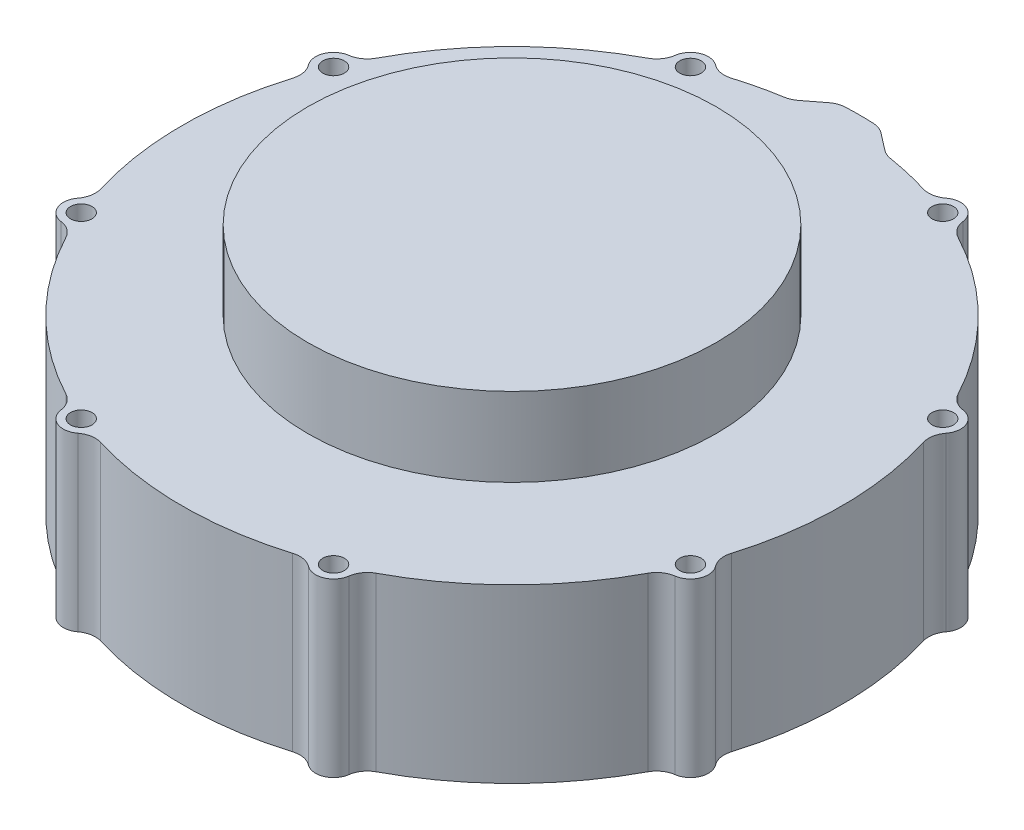
SolidWorks part; units mm, degrees
ref_plane "Спереди" through (0, 0, 0) normal (0, 0, 1) x (1, 0, 0)
ref_plane "Сверху" through (0, 0, 0) normal (0, 1, 0) x (1, 0, 0)
ref_plane "Справа" through (0, 0, 0) normal (1, 0, 0) x (0, 0, -1)
sketch "Эскиз1" plane through (0, 0, 0) normal (0, 1, 0) x (1, 0, 0)
  line L0 (0, 46) -> (0, -46) construction
  line L1 (-46, 0) -> (46, 0) construction
  line L2 (17.6034, 42.4985) -> (0, 0) construction
  line L3 (2.8896, 48.4138) -> (6.6554, 45.516)
  line L4 (-2.8896, 48.4138) -> (-6.6554, 45.516)
  arc A0 (-19.8863, 41.4793) -> (-41.4793, 19.8863) centre (0, 0) ccw
  circle A4 centre (17.6034, 42.4985) radius 1.5
  arc A5 (19.8863, 41.4793) -> (15.2686, 43.3921) centre (17.6034, 42.4985) ccw
  arc A6 (43.3921, 15.2686) -> (41.4793, 19.8863) centre (42.4985, 17.6034) ccw
  circle A7 centre (42.4985, 17.6034) radius 1.5
  arc A8 (41.4793, -19.8863) -> (43.3921, -15.2686) centre (42.4985, -17.6034) ccw
  circle A9 centre (42.4985, -17.6034) radius 1.5
  arc A10 (15.2686, -43.3921) -> (19.8863, -41.4793) centre (17.6034, -42.4985) ccw
  circle A11 centre (17.6034, -42.4985) radius 1.5
  arc A12 (-19.8863, -41.4793) -> (-15.2686, -43.3921) centre (-17.6034, -42.4985) ccw
  circle A13 centre (-17.6034, -42.4985) radius 1.5
  arc A14 (-43.3921, -15.2686) -> (-41.4793, -19.8863) centre (-42.4985, -17.6034) ccw
  circle A15 centre (-42.4985, -17.6034) radius 1.5
  arc A16 (-41.4793, 19.8863) -> (-43.3921, 15.2686) centre (-42.4985, 17.6034) ccw
  circle A17 centre (-42.4985, 17.6034) radius 1.5
  arc A18 (-15.2686, 43.3921) -> (-19.8863, 41.4793) centre (-17.6034, 42.4985) ccw
  circle A19 centre (-17.6034, 42.4985) radius 1.5
  arc A20 (15.2686, 43.3921) -> (6.6554, 45.516) centre (0, 0) ccw
  arc A21 (41.4793, 19.8863) -> (19.8863, 41.4793) centre (0, 0) ccw
  arc A22 (43.3921, -15.2686) -> (43.3921, 15.2686) centre (0, 0) ccw
  arc A23 (19.8863, -41.4793) -> (41.4793, -19.8863) centre (0, 0) ccw
  arc A24 (-15.2686, -43.3921) -> (15.2686, -43.3921) centre (0, 0) ccw
  arc A25 (-41.4793, -19.8863) -> (-19.8863, -41.4793) centre (0, 0) ccw
  arc A26 (-43.3921, 15.2686) -> (-43.3921, -15.2686) centre (0, 0) ccw
  arc A27 (2.8896, 48.4138) -> (-2.8896, 48.4138) centre (0, 0) ccw
  arc A29 (-6.6554, 45.516) -> (-15.2686, 43.3921) centre (0, 0) ccw
  point P35 (0, 0)
  dimension "D1" = 92
  dimension "D3" = 22.5
  dimension "D4" = 8
extrude "Бобышка-Вытянуть1" add sketch "Эскиз1" along normal blind 24
fillet "Скругление2" radius 3 20 edges at (41.4793, 12, -19.8863) (43.3921, 12, -15.2686) (43.3921, 12, 15.2686) (41.4793, 12, 19.8863) (19.8863, 12, 41.4793) (15.2686, 12, 43.3921) (-15.2686, 12, 43.3921) (-19.8863, 12, 41.4793) (-41.4793, 12, 19.8863) (-43.3921, 12, 15.2686) (-43.3921, 12, -15.2686) (-41.4793, 12, -19.8863) (-19.8863, 12, -41.4793) (-15.2686, 12, -43.3921) (-6.6554, 12, -45.516) (-2.8896, 12, -48.4138) (2.8896, 12, -48.4138) (6.6554, 12, -45.516) (15.2686, 12, -43.3921) (19.8863, 12, -41.4793)
sketch "Эскиз2" plane through (0, 24, 0) normal (0, 1, 0) x (1, 0, 0)
  circle A0 centre (0, 0) radius 28.5
  dimension "D1" = 57
extrude "Бобышка-Вытянуть2" add sketch "Эскиз2" along normal blind 11
sketch "Эскиз3" plane through (0, 0, 0) normal (0, -1, 0) x (1, 0, 0)
  circle A0 centre (0, 0) radius 25
  dimension "D1" = 50
extrude "Бобышка-Вытянуть3" add sketch "Эскиз3" along normal blind 4.8 contours A0
sketch "Эскиз4" plane through (0, -4.8, 0) normal (0, -1, 0) x (1, 0, 0)
  circle A0 centre (0, 0) radius 17
  dimension "D1" = 34
extrude "Вырез-Вытянуть1" cut sketch "Эскиз4" against normal blind 15
